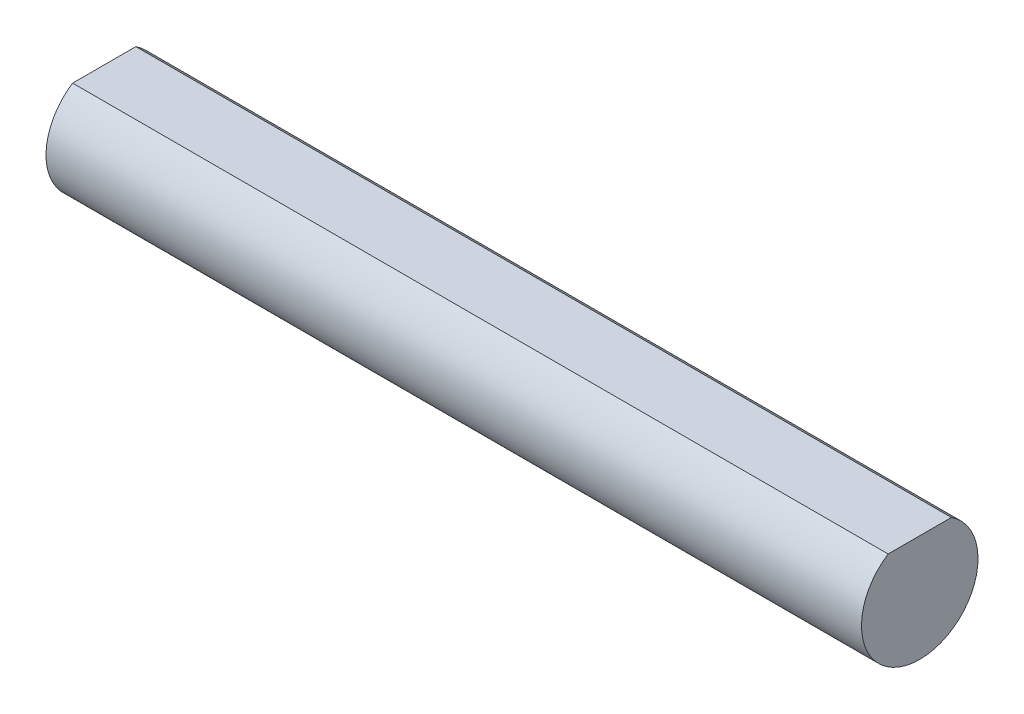
SolidWorks part; units mm, degrees
ref_plane "Front Plane" through (0, 0, 0) normal (0, 0, 1) x (1, 0, 0)
ref_plane "Top Plane" through (0, 0, 0) normal (0, 1, 0) x (1, 0, 0)
ref_plane "Right Plane" through (0, 0, 0) normal (1, 0, 0) x (0, 0, -1)
sketch "Sketch1" plane through (0, 0, 0) normal (1, 0, 0) x (0, 0, -1)
  line L0 (1.3565, 2.1) -> (-1.3565, 2.1)
  arc A0 (-1.3565, 2.1) -> (1.3565, 2.1) centre (0, 0) ccw
  point P5 (-4.3073, 1.1691)
  dimension "D1" = 5
  dimension "D2" = 2.1
extrude "Boss-Extrude1" add sketch "Sketch1" along normal blind 35
